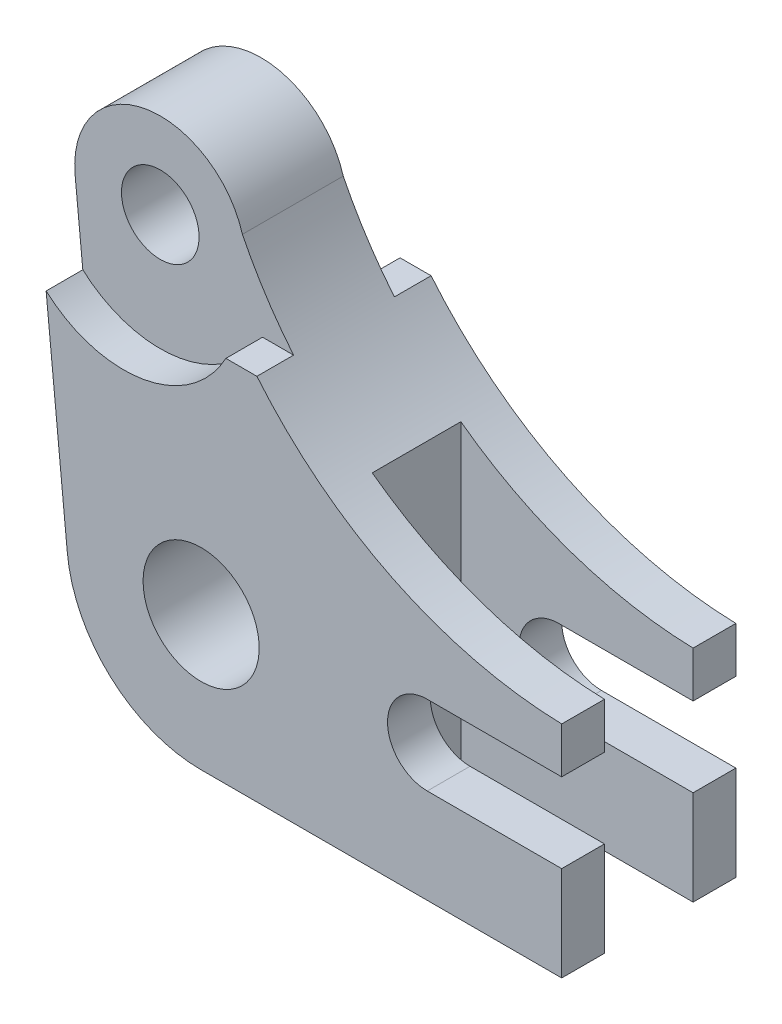
SolidWorks part; units mm, degrees
material "AISI 1020"
ref_plane "Plan de face" through (0, 0, 0) normal (0, 0, 1) x (1, 0, 0)
ref_plane "Plan de dessus" through (0, 0, 0) normal (0, 1, 0) x (1, 0, 0)
ref_plane "Plan de droite" through (0, 0, 0) normal (1, 0, 0) x (0, 0, -1)
sketch "Esquisse1" plane through (0, 0, 0) normal (0, 0, 1) x (1, 0, 0)
  line L0 (-86.6333, -6.9931) -> (-81.9129, -55.1046)
  line L5 (-1.018, -46.4564) -> (-23.018, -46.4564)
  line L7 (-23.018, -59.4564) -> (-1.018, -59.4564)
  line L8 (-1.018, -59.4564) -> (-1.018, -74.9564)
  line L9 (-1.018, -74.9564) -> (-60.018, -74.9564)
  line L13 (-60.018, -52.9564) -> (-60.018, -14.6646) construction
  line L14 (-60.018, -52.9564) -> (-72.7002, -5.6261) construction
  line L15 (-1.018, -46.4564) -> (-1.018, -38.9564)
  arc A0 (-81.9129, -55.1046) -> (-60.018, -74.9564) centre (-60.018, -52.9564) ccw
  arc A3 (-23.018, -59.4564) -> (-23.018, -46.4564) centre (-23.018, -52.9564) cw
  circle A4 centre (-72.7002, -5.6261) radius 6.35
  circle A5 centre (-60.018, -52.9564) radius 9.5
  arc A7 (-1.018, -38.9564) -> (-59.2631, -1.6959) centre (0.7869, 28.0193) cw
  arc A8 (-59.2631, -1.6959) -> (-86.6333, -6.9931) centre (-72.7002, -5.6261) ccw
  point P2 (-47.7667, -14.6646)
  point P3 (0, 0)
  point P12 (-86.6333, -6.9931)
  point P13 (0, 0)
  dimension "D1" = 22
  dimension "D3" = 6.5
  dimension "D4" = 14
  dimension "D10" = 67
  dimension "D15" = 12.7
  dimension "D6" = 59
  dimension "D7" = 22
  dimension "D8" = 49
  dimension "D9" = 0
  dimension "D11" = 0
  dimension "D5" = 0
  dimension "D12" = 15
  dimension "D13" = 22
  dimension "D14" = 0
  dimension "D2" = 36
extrude "Boss.-Extru.1" add sketch "Esquisse1" along normal blind 28.5
sketch "Esquisse2" plane through (0, 0, 28.5) normal (0, 0, 1) x (1, 0, 0)
  line L0 (-50.8888, -14.6261) -> (-55.967, -14.6261)
  line L2 (-86.6333, -6.9931) -> (-81.9129, -55.1046) construction
  line L3 (-86.6333, -6.9931) -> (-85.379, -19.7769)
  arc A0 (-55.967, -14.6261) -> (-85.379, -19.7769) centre (-72.7002, -5.6261) cw
  arc A2 (-59.2631, -1.6959) -> (-1.018, -38.9564) centre (0.7869, 28.0193) ccw construction
  arc A3 (-59.2631, -1.6959) -> (-86.6333, -6.9931) centre (-72.7002, -5.6261) ccw construction
  arc A4 (-59.2631, -1.6959) -> (-50.8888, -14.6261) centre (0.7869, 28.0193) ccw
  arc A5 (-59.2631, -1.6959) -> (-86.6333, -6.9931) centre (-72.7002, -5.6261) ccw
  point P9 (0, 0)
  point P11 (-70.7189, -7.9477)
  point P12 (0, 0)
  dimension "D1" = 19
  dimension "D2" = 9
extrude "Enlèv. mat.-Extru.1" cut sketch "Esquisse2" against normal blind 6
sketch "Esquisse3" plane through (0, 0, 0) normal (0, 0, -1) x (-1, 0, 0)
  line L2 (85.379, -19.7769) -> (86.6333, -6.9931)
  line L3 (50.8888, -14.6261) -> (55.967, -14.6261)
  line L4 (85.379, -19.7769) -> (86.6333, -6.9931)
  line L5 (50.8888, -14.6261) -> (55.967, -14.6261)
  arc A3 (50.8888, -14.6261) -> (59.2631, -1.6959) centre (-0.7869, 28.0193) ccw
  arc A4 (86.6333, -6.9931) -> (59.2631, -1.6959) centre (72.7002, -5.6261) ccw
  arc A5 (55.967, -14.6261) -> (85.379, -19.7769) centre (72.7002, -5.6261) ccw
  arc A6 (50.8888, -14.6261) -> (59.2631, -1.6959) centre (-0.7869, 28.0193) ccw
  arc A7 (86.6333, -6.9931) -> (59.2631, -1.6959) centre (72.7002, -5.6261) ccw
  arc A8 (55.967, -14.6261) -> (85.379, -19.7769) centre (72.7002, -5.6261) ccw
  dimension "D1" = 0
extrude "Enlèv. mat.-Extru.2" cut sketch "Esquisse3" against normal blind 6
sketch "Esquisse4" plane through (0, -74.9564, 0) normal (0, -1, 0) x (1, 0, 0)
  line L0 (-39.018, 7) -> (-39.018, 21.5)
  line L3 (-1.018, 28.5) -> (-1.018, 0) construction
  line L4 (-39.018, 21.5) -> (-1.018, 21.5)
  line L5 (-39.018, 7) -> (-1.018, 7)
  line L6 (-1.018, 7) -> (-1.018, 21.5)
  line L7 (-1.018, 0) -> (-59.2631, 0) construction
  line L8 (-60.018, 28.5) -> (-1.018, 28.5) construction
  dimension "D1" = 38
  dimension "D2" = 7
  dimension "D3" = 7
extrude "Enlèv. mat.-Extru.3" cut sketch "Esquisse4" against normal through all
equation "\"A\"= 59"
equation "\"B\"= 22"
equation "\"C\"= 28.5"
equation "\"D6@Esquisse1\"=\"A\""
equation "\"D1@Esquisse1\"=\"B\""
equation "\"D13@Esquisse1\"=\"B\""
equation "\"D1@Boss.-Extru.1\"=\"C\""
